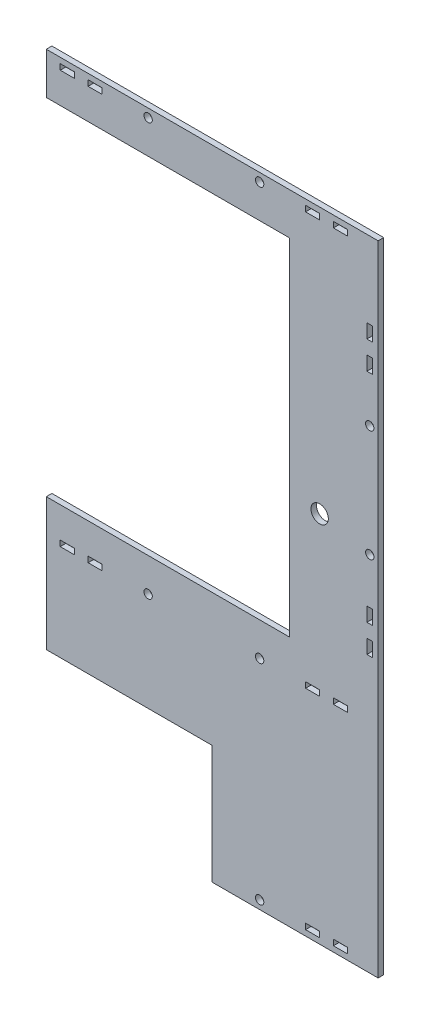
SolidWorks part; units mm, degrees
ref_plane "前视基准面" through (0, 0, 0) normal (0, 0, 1) x (1, 0, 0)
ref_plane "上视基准面" through (0, 0, 0) normal (0, 1, 0) x (1, 0, 0)
ref_plane "右视基准面" through (0, 0, 0) normal (1, 0, 0) x (0, 0, -1)
sketch "草图1" plane through (0, 0, 0) normal (0, 0, 1) x (1, 0, 0)
  line L0 (-46.0613, -2.3972) -> (-51.1113, -0.3472) construction
  line L5 (36.8887, -0.3472) -> (41.9387, -0.3472)
  line L6 (36.8887, -0.3472) -> (36.8887, -2.3972)
  line L11 (36.8887, -2.3972) -> (41.9387, -2.3972)
  line L12 (41.9387, -0.3472) -> (41.9387, -2.3972)
  line L13 (36.8887, -0.3472) -> (41.9387, -2.3972) construction
  line L14 (36.8887, -2.3972) -> (41.9387, -0.3472) construction
  line L15 (46.8887, -0.3472) -> (51.9387, -0.3472)
  line L25 (46.8887, -0.3472) -> (46.8887, -2.3972)
  line L30 (46.8887, -2.3972) -> (51.9387, -2.3972)
  line L31 (51.9387, -0.3472) -> (51.9387, -2.3972)
  line L36 (46.8887, -0.3472) -> (51.9387, -2.3972) construction
  line L37 (46.8887, -2.3972) -> (51.9387, -0.3472) construction
  line L38 (-46.0613, -0.3472) -> (-51.1113, -2.3972) construction
  line L39 (-36.0613, -2.3972) -> (-41.1113, -0.3472) construction
  line L40 (-36.0613, -0.3472) -> (-41.1113, -2.3972) construction
  line L55 (-51.1113, -0.3472) -> (-51.1113, -2.3972)
  line L60 (-46.0613, -2.3972) -> (-51.1113, -2.3972)
  line L61 (-46.0613, -0.3472) -> (-46.0613, -2.3972)
  line L66 (-46.0613, -0.3472) -> (-51.1113, -0.3472)
  line L67 (-41.1113, -0.3472) -> (-41.1113, -2.3972)
  line L68 (-36.0613, -2.3972) -> (-41.1113, -2.3972)
  line L69 (-36.0613, -0.3472) -> (-36.0613, -2.3972)
  line L70 (-36.0613, -0.3472) -> (-41.1113, -0.3472)
  line L81 (-48.5863, -1.3722) -> (49.4137, -1.3722) construction
  line L82 (-19.5863, -149.3722) -> (-8.6103, -149.3722) construction
  line L83 (-46.0613, -150.3972) -> (-51.1113, -148.3472) construction
  line L84 (36.8887, -148.3472) -> (41.9387, -148.3472)
  line L85 (36.8887, -148.3472) -> (36.8887, -150.3972)
  line L86 (36.8887, -150.3972) -> (41.9387, -150.3972)
  line L87 (41.9387, -148.3472) -> (41.9387, -150.3972)
  line L88 (36.8887, -148.3472) -> (41.9387, -150.3972) construction
  line L89 (36.8887, -150.3972) -> (41.9387, -148.3472) construction
  line L90 (46.8887, -148.3472) -> (51.9387, -148.3472)
  line L91 (46.8887, -148.3472) -> (46.8887, -150.3972)
  line L92 (46.8887, -150.3972) -> (51.9387, -150.3972)
  line L93 (51.9387, -148.3472) -> (51.9387, -150.3972)
  line L94 (46.8887, -148.3472) -> (51.9387, -150.3972) construction
  line L95 (46.8887, -150.3972) -> (51.9387, -148.3472) construction
  line L96 (-46.0613, -148.3472) -> (-51.1113, -150.3972) construction
  line L97 (-36.0613, -150.3972) -> (-41.1113, -148.3472) construction
  line L98 (-36.0613, -148.3472) -> (-41.1113, -150.3972) construction
  line L99 (-51.1113, -148.3472) -> (-51.1113, -150.3972)
  line L100 (-46.0613, -150.3972) -> (-51.1113, -150.3972)
  line L101 (-46.0613, -148.3472) -> (-46.0613, -150.3972)
  line L102 (-46.0613, -148.3472) -> (-51.1113, -148.3472)
  line L103 (-41.1113, -148.3472) -> (-41.1113, -150.3972)
  line L104 (-36.0613, -150.3972) -> (-41.1113, -150.3972)
  line L105 (-36.0613, -148.3472) -> (-36.0613, -150.3972)
  line L106 (-36.0613, -148.3472) -> (-41.1113, -148.3472)
  line L107 (59.9198, -57.3722) -> (59.9198, -97.3722) construction
  line L108 (-56.1113, -13.3722) -> (31.071, -13.3722)
  line L109 (-56.1113, 1.6278) -> (62.9198, 1.6278)
  line L110 (-56.1113, 1.6278) -> (-56.1113, -152.3722) construction
  line L111 (-56.1113, -152.3722) -> (62.9198, -152.3722) construction
  line L112 (62.9198, 1.6278) -> (62.9198, -152.3722)
  line L113 (60.9448, -123.8472) -> (58.8948, -128.8972) construction
  line L114 (58.8948, -40.8972) -> (58.8948, -35.8472)
  line L115 (58.8948, -40.8972) -> (60.9448, -40.8972)
  line L116 (60.9448, -40.8972) -> (60.9448, -35.8472)
  line L117 (58.8948, -35.8472) -> (60.9448, -35.8472)
  line L118 (58.8948, -40.8972) -> (60.9448, -35.8472) construction
  line L119 (60.9448, -40.8972) -> (58.8948, -35.8472) construction
  line L120 (58.8948, -30.8972) -> (58.8948, -25.8472)
  line L121 (58.8948, -30.8972) -> (60.9448, -30.8972)
  line L122 (60.9448, -30.8972) -> (60.9448, -25.8472)
  line L123 (58.8948, -25.8472) -> (60.9448, -25.8472)
  line L124 (58.8948, -30.8972) -> (60.9448, -25.8472) construction
  line L125 (60.9448, -30.8972) -> (58.8948, -25.8472) construction
  line L126 (58.8948, -123.8472) -> (60.9448, -128.8972) construction
  line L127 (60.9448, -113.8472) -> (58.8948, -118.8972) construction
  line L128 (58.8948, -113.8472) -> (60.9448, -118.8972) construction
  line L129 (58.8948, -128.8972) -> (60.9448, -128.8972)
  line L130 (60.9448, -123.8472) -> (60.9448, -128.8972)
  line L131 (58.8948, -123.8472) -> (60.9448, -123.8472)
  line L132 (58.8948, -123.8472) -> (58.8948, -128.8972)
  line L133 (58.8948, -118.8972) -> (60.9448, -118.8972)
  line L134 (60.9448, -113.8472) -> (60.9448, -118.8972)
  line L135 (58.8948, -113.8472) -> (60.9448, -113.8472)
  line L136 (58.8948, -113.8472) -> (58.8948, -118.8972)
  line L137 (31.071, -13.3722) -> (31.071, -137.3722)
  line L138 (31.071, -137.3722) -> (-56.1113, -137.3722)
  line L139 (-56.1113, -137.3722) -> (-56.1113, -152.3722)
  line L140 (-56.1113, -13.3722) -> (-56.1113, 1.6278)
  line L141 (20.4137, -149.3722) -> (20.4137, -224.3722) construction
  line L143 (-46.0613, -225.3972) -> (-51.1113, -223.3472) construction
  line L144 (36.8887, -223.3472) -> (41.9387, -223.3472)
  line L145 (36.8887, -223.3472) -> (36.8887, -225.3972)
  line L146 (36.8887, -225.3972) -> (41.9387, -225.3972)
  line L147 (41.9387, -223.3472) -> (41.9387, -225.3972)
  line L148 (36.8887, -223.3472) -> (41.9387, -225.3972) construction
  line L149 (36.8887, -225.3972) -> (41.9387, -223.3472) construction
  line L150 (46.8887, -223.3472) -> (51.9387, -223.3472)
  line L151 (46.8887, -223.3472) -> (46.8887, -225.3972)
  line L152 (46.8887, -225.3972) -> (51.9387, -225.3972)
  line L153 (51.9387, -223.3472) -> (51.9387, -225.3972)
  line L154 (46.8887, -223.3472) -> (51.9387, -225.3972) construction
  line L155 (46.8887, -225.3972) -> (51.9387, -223.3472) construction
  line L156 (-46.0613, -223.3472) -> (-51.1113, -225.3972) construction
  line L157 (-36.0613, -225.3972) -> (-41.1113, -223.3472) construction
  line L158 (-36.0613, -223.3472) -> (-41.1113, -225.3972) construction
  line L159 (-51.1113, -223.3472) -> (-51.1113, -225.3972)
  line L160 (-46.0613, -225.3972) -> (-51.1113, -225.3972)
  line L161 (-46.0613, -223.3472) -> (-46.0613, -225.3972)
  line L162 (-46.0613, -223.3472) -> (-51.1113, -223.3472)
  line L163 (-41.1113, -223.3472) -> (-41.1113, -225.3972)
  line L164 (-36.0613, -225.3972) -> (-41.1113, -225.3972)
  line L165 (-36.0613, -223.3472) -> (-36.0613, -225.3972)
  line L166 (-36.0613, -223.3472) -> (-41.1113, -223.3472)
  line L167 (-56.1113, -152.3722) -> (-56.1113, -227.3972)
  line L168 (-56.1113, -227.3972) -> (62.9198, -227.3972)
  line L169 (62.9198, -227.3972) -> (62.9198, -152.3722)
  circle A6 centre (-19.5863, -1.3722) radius 1.5
  circle A7 centre (20.4137, -1.3722) radius 1.5
  circle A9 centre (-19.5863, -149.3722) radius 1.5
  circle A10 centre (20.4137, -149.3722) radius 1.5
  circle A11 centre (59.9198, -97.3722) radius 1.5
  circle A12 centre (59.9198, -57.3722) radius 1.5
  circle A13 centre (41.9387, -93.6781) radius 3.1213
  circle A14 centre (-19.5863, -224.3722) radius 1.5
  circle A15 centre (20.4137, -224.3722) radius 1.5
  point P8 (-38.5863, -1.3722)
  point P13 (39.4137, -1.3722)
  point P35 (-38.5863, -149.3722)
  point P40 (39.4137, -149.3722)
  point P54 (3.4042, -152.3722)
  point P80 (101.1063, -340.4435)
  point P91 (-38.5863, -224.3722)
  point P96 (39.4137, -224.3722)
  dimension "D1" = 148
  dimension "D2" = 3
  dimension "D4" = 3
  dimension "D5" = 5
  dimension "D6" = 15
  dimension "D7" = 15
extrude "凸台-拉伸1" add sketch "草图1" along normal blind 2
sketch "草图2" plane through (0, 0, 2) normal (0, 0, 1) x (1, 0, 0)
  line L0 (3.4042, -227.3972) -> (3.4042, -184.9028)
  line L1 (-56.1113, -227.3972) -> (62.9198, -227.3972) construction
  line L2 (3.4042, -184.9028) -> (-56.1113, -184.9028)
  line L3 (-56.1113, -137.3722) -> (-56.1113, -227.3972) construction
  line L4 (-56.1113, -184.9028) -> (-56.1113, -227.3972)
  line L5 (-56.1113, -227.3972) -> (3.4042, -227.3972)
extrude "切除-拉伸1" cut sketch "草图2" against normal blind 10
